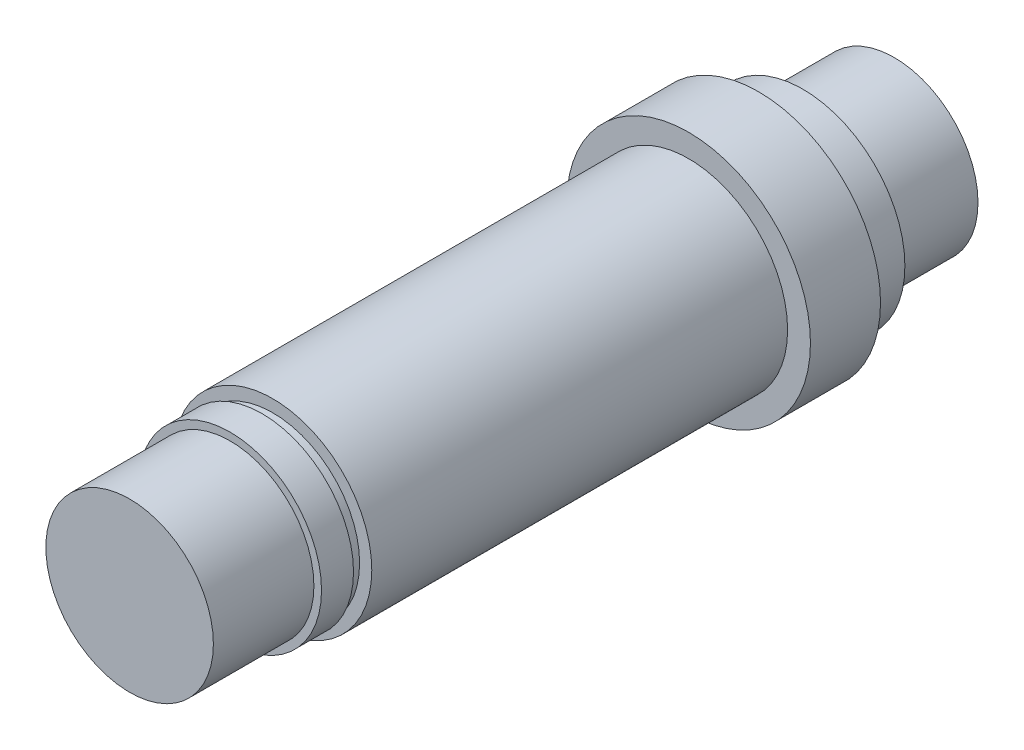
SolidWorks part; units mm, degrees
ref_plane "前视基准面" through (0, 0, 0) normal (0, 0, 1) x (1, 0, 0)
ref_plane "上视基准面" through (0, 0, 0) normal (0, 1, 0) x (1, 0, 0)
ref_plane "右视基准面" through (0, 0, 0) normal (1, 0, 0) x (0, 0, -1)
sketch "草图1" plane through (0, 0, 0) normal (1, 0, 0) x (0, 0, -1)
  line L0 (-1000, 0) -> (49000, 0) construction
  line L1 (0, 0) -> (251, 0)
  line L2 (0, 0) -> (0, 27.5)
  line L3 (0, 27.5) -> (33, 27.5)
  line L4 (33, 27.5) -> (33, 30)
  line L5 (33, 30) -> (43.5, 30)
  line L6 (43.5, 30) -> (43.5, 28.5)
  line L7 (43.5, 28.5) -> (47, 28.5)
  line L8 (47, 28.5) -> (47, 32.5)
  line L9 (0, -1000) -> (0, 49000) construction
  line L10 (47, 32.5) -> (183.5, 32.5)
  line L11 (183.5, 32.5) -> (183.5, 40)
  line L12 (183.5, 40) -> (206.5, 40)
  line L13 (206.5, 40) -> (206.5, 33.5)
  line L14 (206.5, 33.5) -> (221, 33.5)
  line L15 (221, 33.5) -> (221, 27.5)
  line L16 (221, 27.5) -> (251, 27.5)
  line L17 (251, 27.5) -> (251, 0)
  dimension "D1" = 251
  dimension "D2" = 27.5
  dimension "D3" = 33
  dimension "D4" = 10.5
  dimension "D5" = 30
  dimension "D6" = 3.5
  dimension "D7" = 1.5
  dimension "D8" = 32.5
  dimension "D9" = 136.5
  dimension "D10" = 40
  dimension "D11" = 23
  dimension "D12" = 33.5
  dimension "D13" = 27.5
  dimension "D14" = 30
revolve "旋转2" add sketch "草图1" angle 360 about L0
